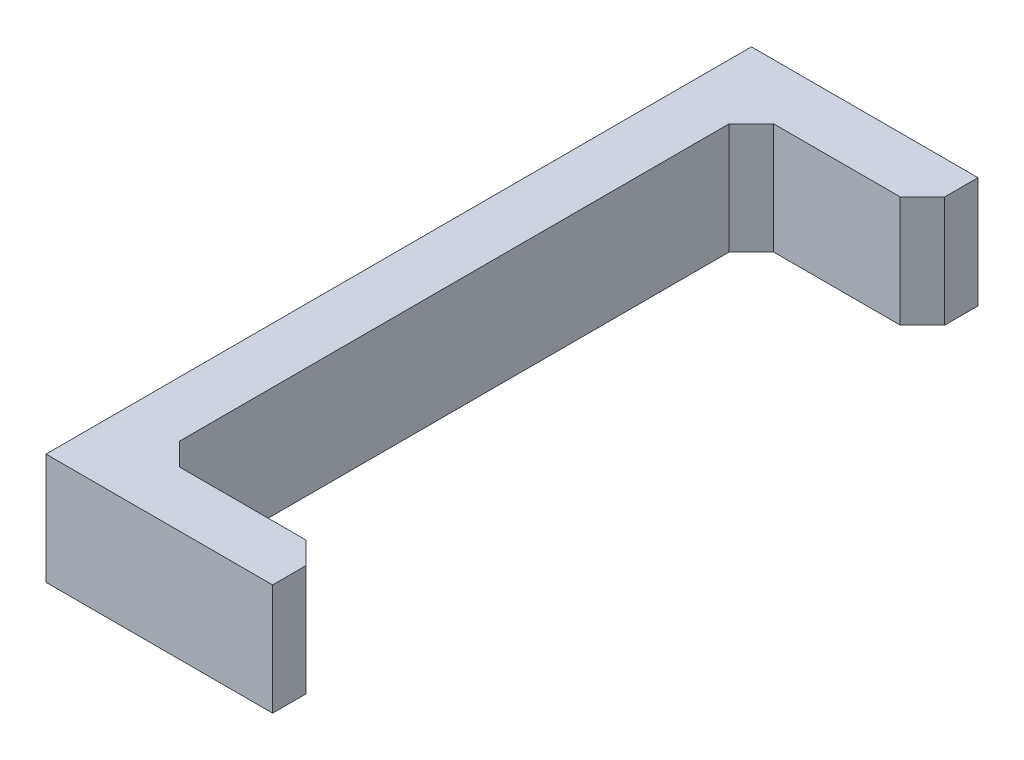
SolidWorks part; units mm, degrees
ref_plane "Front Plane" through (0, 0, 0) normal (0, 0, 1) x (1, 0, 0)
ref_plane "Top Plane" through (0, 0, 0) normal (0, 1, 0) x (1, 0, 0)
ref_plane "Right Plane" through (0, 0, 0) normal (1, 0, 0) x (0, 0, -1)
sketch "Sketch1" plane through (0, 0, 0) normal (0, 1, 0) x (1, 0, 0)
  line L0 (7.7, 26.75) -> (-7.7, 26.75)
  line L1 (7.7, -31.75) -> (-12.7, -31.75)
  line L2 (7.7, -26.75) -> (7.7, -31.75)
  line L3 (7.7, 31.75) -> (-12.7, 31.75)
  line L4 (-12.7, -31.75) -> (-12.7, 31.75)
  line L5 (12.7, -31.75) -> (-12.7, 31.75) construction
  line L6 (12.7, 31.75) -> (-12.7, -31.75) construction
  line L7 (-7.7, -26.75) -> (-7.7, 26.75)
  line L8 (7.7, -26.75) -> (-7.7, -26.75)
  line L10 (7.7, 31.75) -> (7.7, 26.75)
  line L11 (12.7, -31.75) -> (12.7, 31.75) construction
  line L12 (12.7, -31.75) -> (-12.7, -31.75) construction
  line L13 (12.7, 31.75) -> (-12.7, 31.75) construction
  line L14 (7.7, -26.75) -> (7.7, 26.75) construction
  point P0 (0, 0)
  dimension "D1" = 63.5
  dimension "D2" = 25.4
  dimension "D3" = 5
extrude "Boss-Extrude1" add sketch "Sketch1" along normal blind 10
chamfer "Chamfer1" distance 2 angle 45 4 edges at (7.7, 5, -26.75) (7.7, 5, 26.75) (-7.7, 5, 26.75) (-7.7, 5, -26.75)
